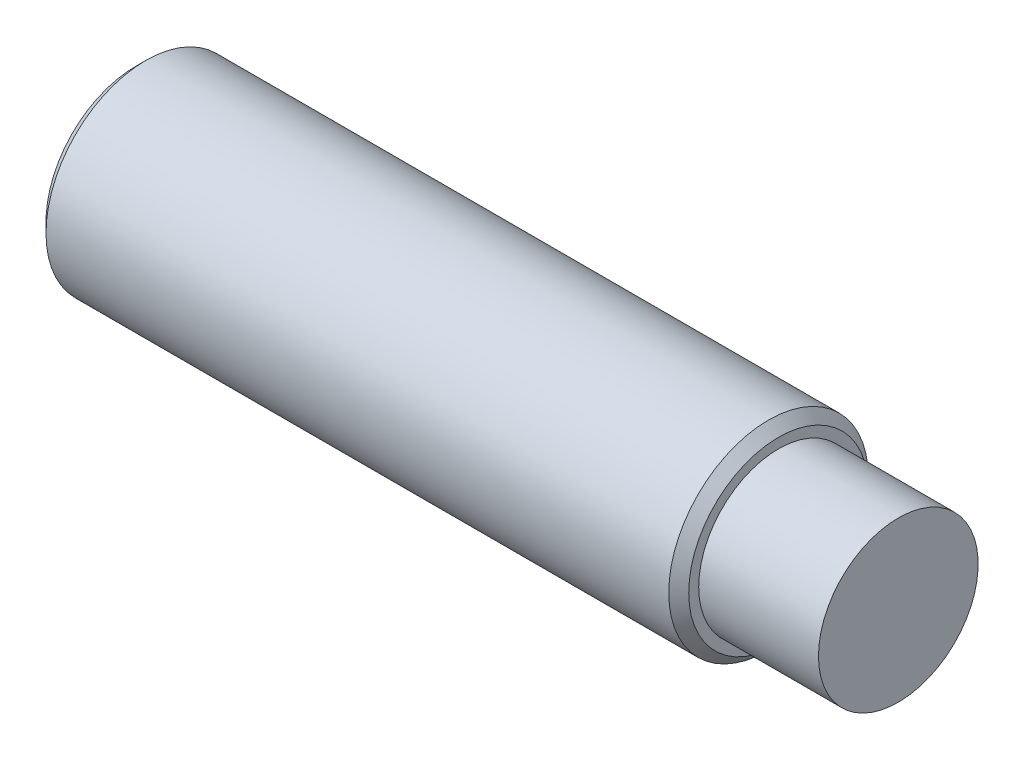
SolidWorks part; units mm, degrees
ref_plane "Front Plane" through (0, 0, 0) normal (0, 0, 1) x (1, 0, 0)
ref_plane "Top Plane" through (0, 0, 0) normal (0, 1, 0) x (1, 0, 0)
ref_plane "Right Plane" through (0, 0, 0) normal (1, 0, 0) x (0, 0, -1)
sketch "Sketch1" plane through (0, 0, 0) normal (0, 0, 1) x (1, 0, 0)
  line L0 (0, 0) -> (0, 5)
  line L1 (0, 5) -> (32.2, 5)
  line L2 (32.2, 5) -> (32.2, 4)
  line L3 (32.2, 4) -> (38.2, 4)
  line L4 (38.2, 4) -> (38.2, 0)
  line L5 (38.2, 0) -> (0, 0)
  line L6 (-21.6251, 0) -> (57.019, 0) construction
  dimension "D1" = 32.2
  dimension "D2" = 6
  dimension "D3" = 10
  dimension "D4" = 8
revolve "Revolve1" add sketch "Sketch1" angle 360 about L6
chamfer "Chamfer1" distance 0.5 angle 45 2 edges at (32.2, 0, 5) (0, 0, 5)
sketch "Sketch6" plane through (0, 0, 0) normal (-1, 0, 0) x (0, 0, 1)
  circle A0 centre (0, 0) radius 2
  dimension "D1" = 4
extrude "Cut-Extrude1" cut sketch "Sketch6" against normal blind 10
